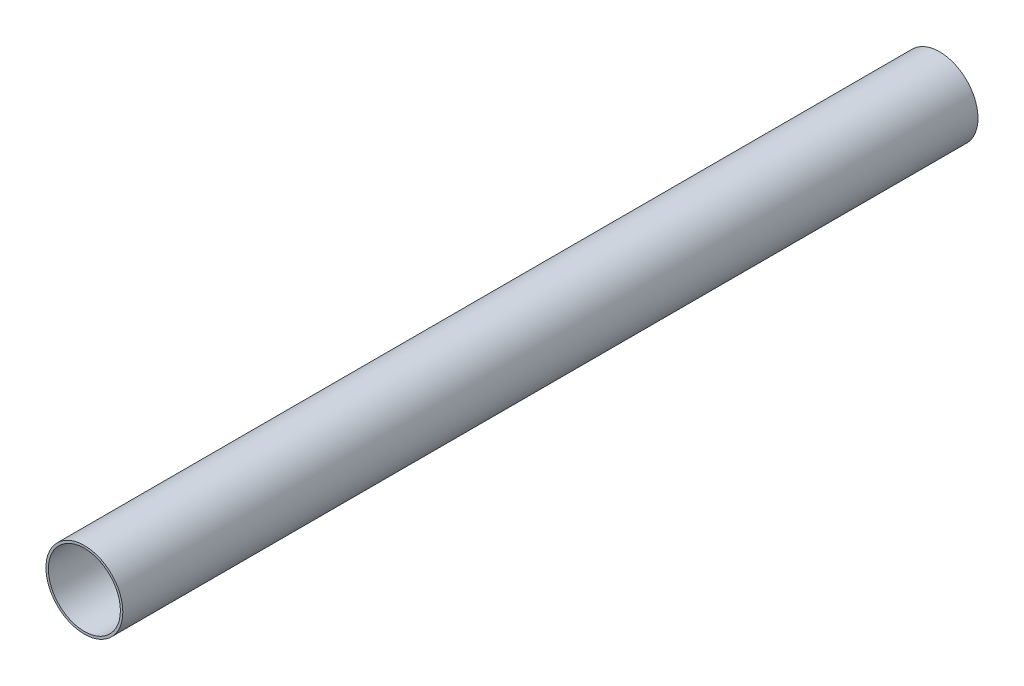
SolidWorks part; units mm, degrees
material "PC High Viscosity"
ref_plane "Front Plane" through (0, 0, 0) normal (0, 0, 1) x (1, 0, 0)
ref_plane "Top Plane" through (0, 0, 0) normal (0, 1, 0) x (1, 0, 0)
ref_plane "Right Plane" through (0, 0, 0) normal (1, 0, 0) x (0, 0, -1)
sketch "Sketch1" plane through (0, 0, 0) normal (0, 0, 1) x (1, 0, 0)
  circle A0 centre (0, 0) radius 23.8125
  circle A1 centre (0, 0) radius 25.4
  dimension "D1" = 50.8
  dimension "D2" = 47.625
extrude "Boss-Extrude1" add sketch "Sketch1" along normal mid plane 565.213
equation "\"D1@Boss-Extrude1\"=21.125in+3.625mm"
